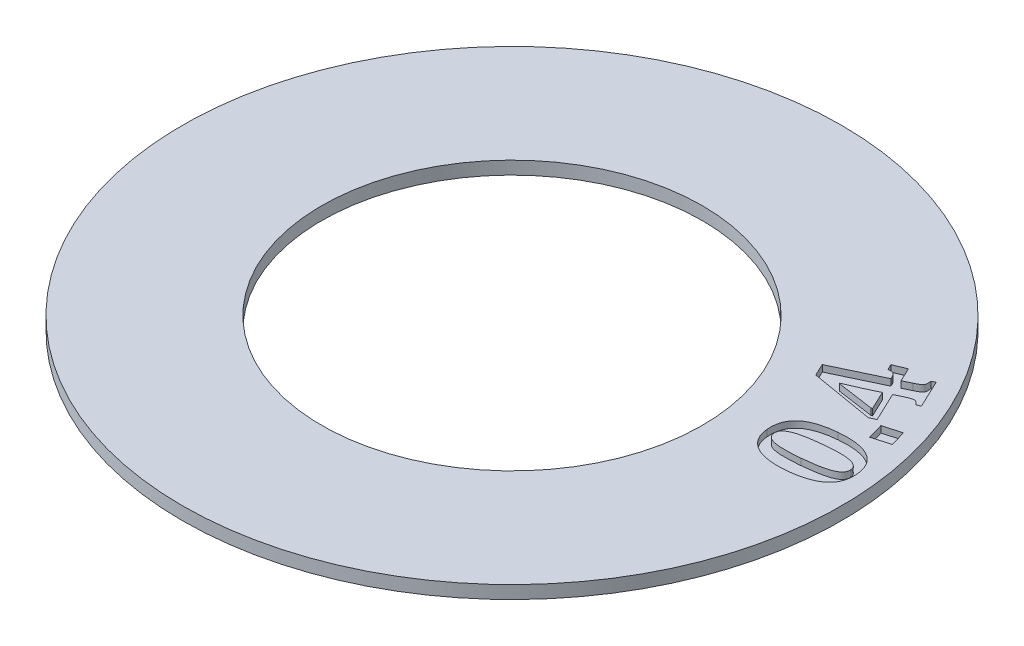
SolidWorks part; units mm, degrees
ref_plane "Front Plane" through (0, 0, 0) normal (0, 0, 1) x (1, 0, 0)
ref_plane "Top Plane" through (0, 0, 0) normal (0, 1, 0) x (1, 0, 0)
ref_plane "Right Plane" through (0, 0, 0) normal (1, 0, 0) x (0, 0, -1)
sketch "Sketch1" plane through (0, 0, 0) normal (0, 1, 0) x (1, 0, 0)
  circle A0 centre (0, 0) radius 10.16
  dimension "D1" = 20.32
extrude "Boss-Extrude1" add sketch "Sketch1" along normal blind 0.4
sketch "Sketch2" plane through (0, 0, 0) normal (0, -1, 0) x (-1, 0, 0)
  circle A0 centre (0, 0) radius 5.8674
  dimension "D1" = 11.7348
extrude "Cut-Extrude1" cut sketch "Sketch2" against normal through all
sketch "Sketch4" plane through (0, 0.4, 0) normal (0, 1, 0) x (1, 0, 0)
  circle A0 centre (0, 0) radius 9.6225 construction
  text T0 "<b>0.4</b>" font "Cambria" height 2.54
extrude "Cut-Extrude2" cut sketch "Sketch4" against normal blind 0.2
